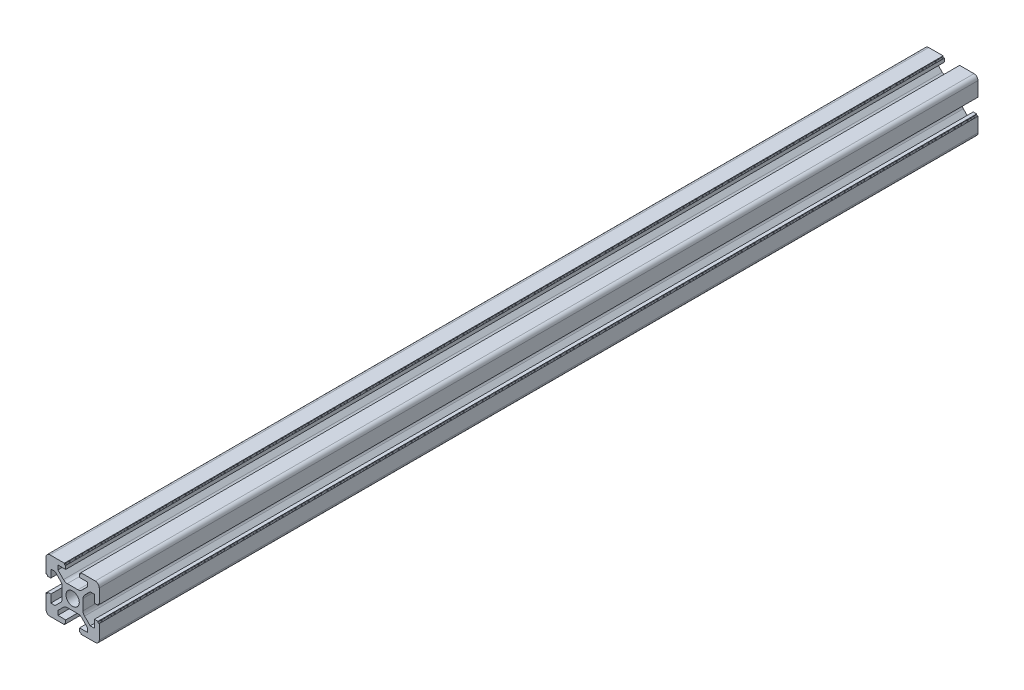
SolidWorks part; units mm, degrees
ref_plane "Спереди" through (0, 0, 0) normal (0, 0, 1) x (1, 0, 0)
ref_plane "Сверху" through (0, 0, 0) normal (0, 1, 0) x (1, 0, 0)
ref_plane "Справа" through (0, 0, 0) normal (1, 0, 0) x (0, 0, -1)
sketch "Sketch1" plane through (0, 0, 0) normal (0, 0, 1) x (1, 0, 0)
  line L0 (0, 10) -> (0, -10) construction
  line L1 (-10, -10) -> (10, -10) construction
  line L2 (-10, -10) -> (-10, 10) construction
  line L3 (-10, 10) -> (10, 10) construction
  line L4 (10, -10) -> (10, 10) construction
  line L5 (-10, -10) -> (10, 10) construction
  line L6 (-10, 10) -> (10, -10) construction
  line L7 (-10, 0) -> (10, 0) construction
  line L8 (0, 3.9) -> (-2.0109, 3.9)
  line L9 (-3.4251, 4.4858) -> (-5.5393, 6.6)
  line L10 (-5.5393, 6.6) -> (-5.5393, 8.2)
  line L11 (-5.5393, 8.2) -> (-2.6, 8.2)
  line L12 (-2.6, 8.2) -> (-2.6, 9.5)
  line L13 (-2.6, 9.5) -> (-2.9, 9.5)
  line L14 (-3.1, 9.7) -> (-3.1, 10)
  line L15 (-3.1, 10) -> (-8.5, 10)
  line L16 (-10, 3.1) -> (-10, 8.5)
  line L17 (-9.7, 3.1) -> (-10, 3.1)
  line L18 (-9.5, 2.6) -> (-9.5, 2.9)
  line L19 (-8.2, 2.6) -> (-9.5, 2.6)
  line L20 (-8.2, 5.5393) -> (-8.2, 2.6)
  line L21 (-6.6, 5.5393) -> (-8.2, 5.5393)
  line L22 (-4.4858, 3.4251) -> (-6.6, 5.5393)
  line L23 (-3.9, 0) -> (-3.9, 2.0109)
  line L24 (3.9, 0) -> (3.9, 2.0109)
  line L25 (4.4858, 3.4251) -> (6.6, 5.5393)
  line L26 (6.6, 5.5393) -> (8.2, 5.5393)
  line L27 (8.2, 5.5393) -> (8.2, 2.6)
  line L28 (8.2, 2.6) -> (9.5, 2.6)
  line L29 (9.5, 2.6) -> (9.5, 2.9)
  line L30 (9.7, 3.1) -> (10, 3.1)
  line L31 (10, 3.1) -> (10, 8.5)
  line L32 (3.1, 10) -> (8.5, 10)
  line L33 (3.1, 9.7) -> (3.1, 10)
  line L34 (2.6, 9.5) -> (2.9, 9.5)
  line L35 (2.6, 8.2) -> (2.6, 9.5)
  line L36 (5.5393, 8.2) -> (2.6, 8.2)
  line L37 (5.5393, 6.6) -> (5.5393, 8.2)
  line L38 (3.4251, 4.4858) -> (5.5393, 6.6)
  line L39 (0, 3.9) -> (2.0109, 3.9)
  line L40 (0, -3.9) -> (2.0109, -3.9)
  line L41 (3.4251, -4.4858) -> (5.5393, -6.6)
  line L42 (5.5393, -6.6) -> (5.5393, -8.2)
  line L43 (5.5393, -8.2) -> (2.6, -8.2)
  line L44 (2.6, -8.2) -> (2.6, -9.5)
  line L45 (2.6, -9.5) -> (2.9, -9.5)
  line L46 (3.1, -9.7) -> (3.1, -10)
  line L47 (3.1, -10) -> (8.5, -10)
  line L48 (10, -3.1) -> (10, -8.5)
  line L49 (9.7, -3.1) -> (10, -3.1)
  line L50 (9.5, -2.6) -> (9.5, -2.9)
  line L51 (8.2, -2.6) -> (9.5, -2.6)
  line L52 (8.2, -5.5393) -> (8.2, -2.6)
  line L53 (6.6, -5.5393) -> (8.2, -5.5393)
  line L54 (4.4858, -3.4251) -> (6.6, -5.5393)
  line L55 (3.9, 0) -> (3.9, -2.0109)
  line L56 (-3.9, 0) -> (-3.9, -2.0109)
  line L57 (-4.4858, -3.4251) -> (-6.6, -5.5393)
  line L58 (-6.6, -5.5393) -> (-8.2, -5.5393)
  line L59 (-8.2, -5.5393) -> (-8.2, -2.6)
  line L60 (-8.2, -2.6) -> (-9.5, -2.6)
  line L61 (-9.5, -2.6) -> (-9.5, -2.9)
  line L62 (-9.7, -3.1) -> (-10, -3.1)
  line L63 (-10, -3.1) -> (-10, -8.5)
  line L64 (-3.1, -10) -> (-8.5, -10)
  line L65 (-3.1, -9.7) -> (-3.1, -10)
  line L66 (-2.6, -9.5) -> (-2.9, -9.5)
  line L67 (-2.6, -8.2) -> (-2.6, -9.5)
  line L68 (-5.5393, -8.2) -> (-2.6, -8.2)
  line L69 (-5.5393, -6.6) -> (-5.5393, -8.2)
  line L70 (-3.4251, -4.4858) -> (-5.5393, -6.6)
  line L71 (0, -3.9) -> (-2.0109, -3.9)
  circle A0 centre (0, 0) radius 2.5
  arc A1 (-8.5, 10) -> (-10, 8.5) centre (-8.5, 8.5) ccw
  arc A2 (-2.0109, 3.9) -> (-3.4251, 4.4858) centre (-2.0109, 5.9) cw
  arc A3 (-2.9, 9.5) -> (-3.1, 9.7) centre (-2.9, 9.7) cw
  arc A4 (-9.5, 2.9) -> (-9.7, 3.1) centre (-9.7, 2.9) ccw
  arc A5 (-3.9, 2.0109) -> (-4.4858, 3.4251) centre (-5.9, 2.0109) ccw
  arc A6 (10, 8.5) -> (8.5, 10) centre (8.5, 8.5) ccw
  arc A7 (3.9, 2.0109) -> (4.4858, 3.4251) centre (5.9, 2.0109) cw
  arc A8 (9.5, 2.9) -> (9.7, 3.1) centre (9.7, 2.9) cw
  arc A9 (2.9, 9.5) -> (3.1, 9.7) centre (2.9, 9.7) ccw
  arc A10 (2.0109, 3.9) -> (3.4251, 4.4858) centre (2.0109, 5.9) ccw
  arc A11 (8.5, -10) -> (10, -8.5) centre (8.5, -8.5) ccw
  arc A12 (2.0109, -3.9) -> (3.4251, -4.4858) centre (2.0109, -5.9) cw
  arc A13 (2.9, -9.5) -> (3.1, -9.7) centre (2.9, -9.7) cw
  arc A14 (9.5, -2.9) -> (9.7, -3.1) centre (9.7, -2.9) ccw
  arc A15 (3.9, -2.0109) -> (4.4858, -3.4251) centre (5.9, -2.0109) ccw
  arc A16 (-10, -8.5) -> (-8.5, -10) centre (-8.5, -8.5) ccw
  arc A17 (-3.9, -2.0109) -> (-4.4858, -3.4251) centre (-5.9, -2.0109) cw
  arc A18 (-9.5, -2.9) -> (-9.7, -3.1) centre (-9.7, -2.9) cw
  arc A19 (-2.9, -9.5) -> (-3.1, -9.7) centre (-2.9, -9.7) ccw
  arc A20 (-2.0109, -3.9) -> (-3.4251, -4.4858) centre (-2.0109, -5.9) ccw
  point P0 (0, 0)
  point P42 (0, 0)
  point P70 (0, 0)
  point P98 (0, 0)
  point P126 (0, 0)
  dimension "D3" = 5
  dimension "D4" = 3
  dimension "D12" = 2
  dimension "D13" = 0.2
  dimension "D1" = 20
  dimension "D2" = 20
  dimension "D5" = 5.2
  dimension "D6" = 6.2
  dimension "D7" = 1.8
  dimension "D8" = 0.5
  dimension "D9" = 3.4
  dimension "D10" = 1.5
  dimension "D11" = 6.1
  dimension "D14" = 4
extrude "Extrude1" add sketch "Sketch1" along normal blind 330
